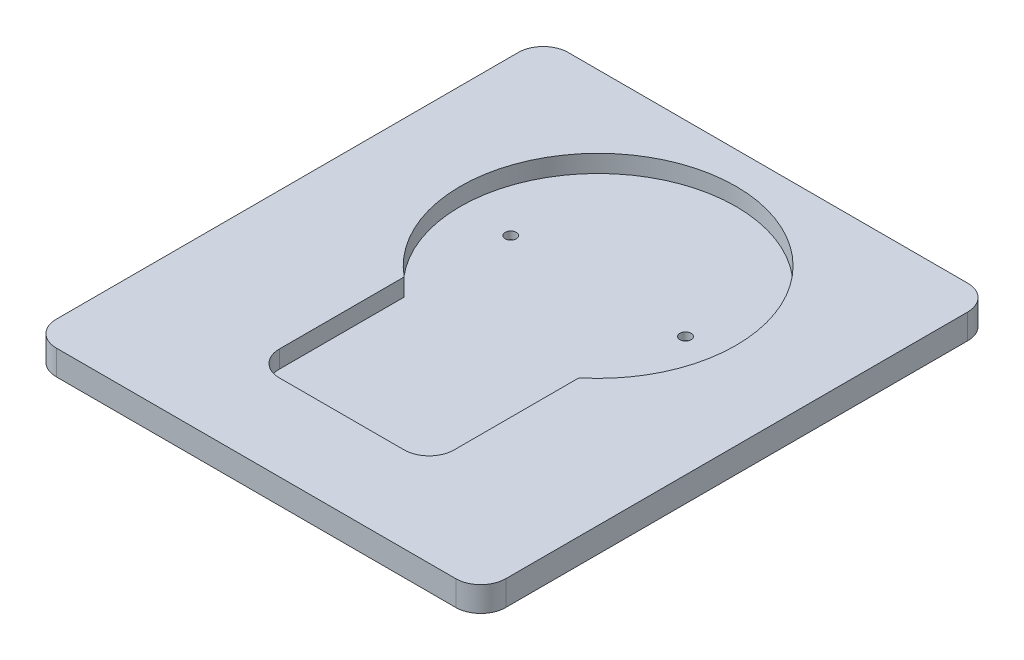
SolidWorks part; units mm, degrees
ref_plane "Plan de face" through (0, 0, 0) normal (0, 0, 1) x (1, 0, 0)
ref_plane "Plan de dessus" through (0, 0, 0) normal (0, 1, 0) x (1, 0, 0)
ref_plane "Plan de droite" through (0, 0, 0) normal (1, 0, 0) x (0, 0, -1)
sketch "Esquisse2" plane through (0, 0, 0) normal (0, 1, 0) x (1, 0, 0)
  line L0 (0, 102.5) -> (0, -102.5) construction
  line L1 (-80, 102.5) -> (80, 102.5)
  line L2 (-90, 92.5) -> (-90, -92.5)
  line L3 (-80, -102.5) -> (80, -102.5)
  line L4 (90, 92.5) -> (90, -92.5)
  line L5 (-90, 0) -> (90, 0) construction
  arc A1 (80, 102.5) -> (90, 92.5) centre (80, 92.5) cw
  arc A2 (80, -102.5) -> (90, -92.5) centre (80, -92.5) ccw
  arc A3 (-90, -92.5) -> (-80, -102.5) centre (-80, -92.5) ccw
  arc A4 (-80, 102.5) -> (-90, 92.5) centre (-80, 92.5) ccw
  point P4 (0, 0)
  dimension "D1" = 205
  dimension "D2" = 10
  dimension "D3" = 180
extrude "Boss.-Extru.1" add sketch "Esquisse2" along normal blind 10
sketch "Esquisse12" plane through (0, 10, 0) normal (0, 1, 0) x (1, 0, 0)
  line L0 (-90, -92.5) -> (90, -92.5) construction
  line L1 (-90, 92.5) -> (-90, -92.5) construction
  line L2 (90, -92.5) -> (90, 92.5) construction
  line L3 (-80, -102.5) -> (80, -102.5) construction
  text T0 "COCO BONBON" font "Comic Sans MS" height in points 72
  dimension "D1" = 10
sketch "Esquisse3" plane through (0, 10, 0) normal (0, 1, 0) x (1, 0, 0)
  line L0 (90, -8.1854) -> (-90, -8.1854) construction
  line L5 (0, 102.5) -> (0, -102.5) construction
  line L6 (-80, -102.5) -> (80, -102.5) construction
  line L9 (-35, -8.1854) -> (-35, -58.1854)
  line L10 (-25, -68.1854) -> (25, -68.1854)
  line L11 (35, -8.1854) -> (35, -58.1854)
  line L12 (80, 102.5) -> (-80, 102.5) construction
  line L13 (-90, 34.5) -> (90, 34.5) construction
  line L14 (-90, 92.5) -> (-90, -92.5) construction
  line L15 (90, -92.5) -> (90, 92.5) construction
  arc A6 (35, -8.1854) -> (-35, -8.1854) centre (0, 34.5) ccw
  arc A7 (-35, -58.1854) -> (-25, -68.1854) centre (-25, -58.1854) ccw
  arc A8 (25, -68.1854) -> (35, -58.1854) centre (25, -58.1854) ccw
  point P1 (0, -68.1854)
  point P16 (0, 34.5)
  dimension "D1" = 110.4
  dimension "D2" = 68
  dimension "D5" = 10
  dimension "D3" = 60
  dimension "D4" = 70
extrude "Enlèv. mat.-Extru.1" cut sketch "Esquisse3" against normal blind 7
hole_wizard "Dégagement M41" positions "Esquisse10" profile "Esquisse11" hole size "M4" standard "ISO"
sketch "Esquisse10" plane through (0, 0, 0) normal (0, -1, 0) x (-1, 0, 0)
  circle A0 centre (0, 34.5) radius 35 construction
  arc A1 (35, -8.1854) -> (-35, -8.1854) centre (0, 34.5) ccw construction
  arc A2 (35, -8.1854) -> (-35, -8.1854) centre (0, 34.5) ccw construction
  point P8 (-35, 34.5)
  point P10 (35, 34.5)
  dimension "D3" = 70
sketch "Esquisse11" plane through (-35, 0, -34.5) normal (1, 0, 0) x (0, 0, -1)
  line L0 (0, 0) -> (0, 11.3519)
  line L1 (0, 11.3519) -> (2.25, 10)
  line L2 (2.25, 10) -> (2.25, 0)
  line L5 (2.25, 0) -> (0, 0)
  line L10 (0, 11.3519) -> (-2.25, 10) construction
  line L11 (0, -6.35) -> (0, 107.95) construction
  dimension "Diamètre du perçage" = 4.5
  dimension "Profondeur du perçage" = 10
  dimension "Angle de pointe" = 118
